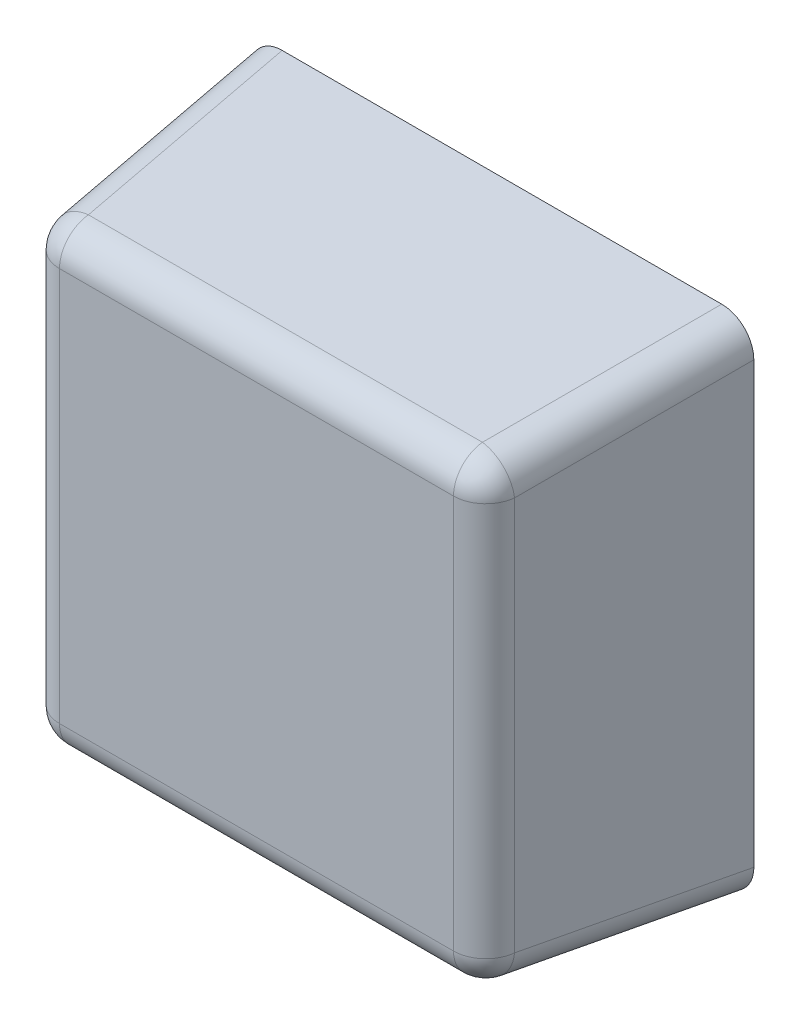
SolidWorks part; units mm, degrees
material "Rubber"
ref_plane "Front Plane" through (0, 0, 0) normal (0, 0, 1) x (1, 0, 0)
ref_plane "Top Plane" through (0, 0, 0) normal (0, 1, 0) x (1, 0, 0)
ref_plane "Right Plane" through (0, 0, 0) normal (1, 0, 0) x (0, 0, -1)
sketch "Sketch1" plane through (0, 0, 0) normal (0, 0, 1) x (1, 0, 0)
  line L1 (0, 0) -> (19.812, 0)
  line L2 (0, 0) -> (0, -19.812)
  line L3 (0, -19.812) -> (19.812, -19.812)
  line L4 (19.812, 0) -> (19.812, -19.812)
  dimension "D1" = 19.812
  dimension "D2" = 19.812
extrude "Boss-Extrude1" add sketch "Sketch1" along normal blind 9.652 draft 6
fillet "Fillet1" radius 1.27 8 edges at (9.906, -1.0145, 9.652) (18.7975, -9.906, 9.652) (9.906, -18.7975, 9.652) (1.0145, -9.906, 9.652) (19.3048, -19.3048, 4.826) (0.5072, -19.3048, 4.826) (0.5072, -0.5072, 4.826) (19.3048, -0.5072, 4.826)
equation "\"D2@Sketch1\"=\"D1@Sketch1\""
